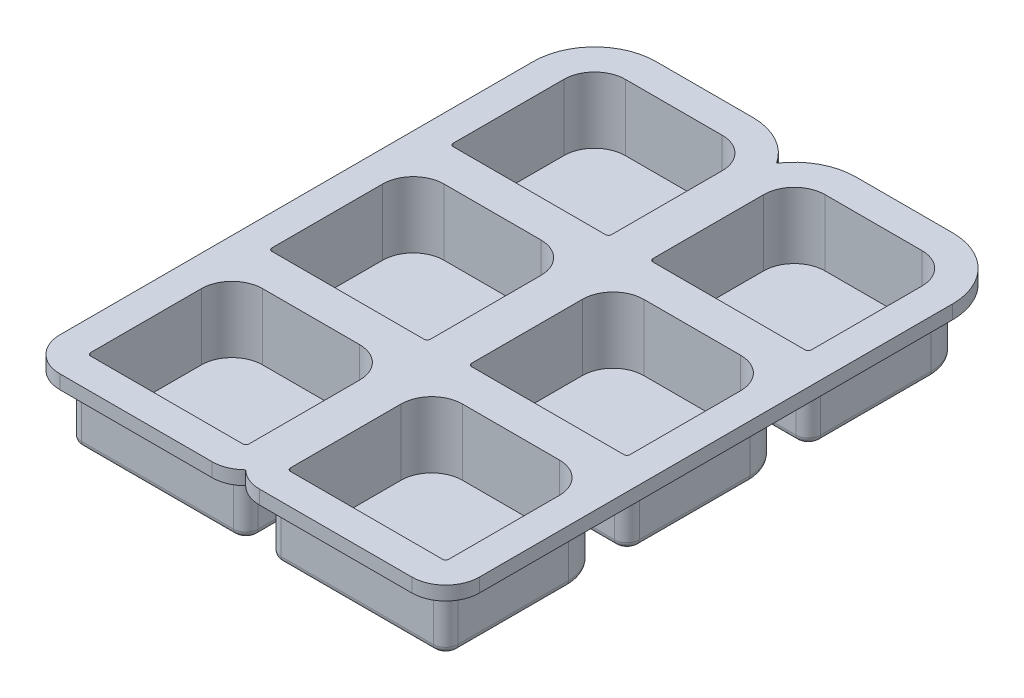
SolidWorks part; units mm, degrees
ref_plane "Alzado" through (0, 0, 0) normal (0, 0, 1) x (1, 0, 0)
ref_plane "Planta" through (0, 0, 0) normal (0, 1, 0) x (1, 0, 0)
ref_plane "Vista lateral" through (0, 0, 0) normal (1, 0, 0) x (0, 0, -1)
sketch "Croquis1" plane through (0, 0, 0) normal (0, 1, 0) x (1, 0, 0)
  line L0 (-48.265, 82.5) -> (-16.735, 82.5)
  line L1 (-6.735, 72.5) -> (-6.735, 36.5)
  line L2 (-7.735, 35.5) -> (-57.265, 35.5)
  line L3 (-58.265, 36.5) -> (-58.265, 72.5)
  line L4 (-32.5, 35.5) -> (-32.5, 82.5) construction
  line L5 (0, 97.5) -> (0, -97.5) construction
  line L6 (16.735, 82.5) -> (48.265, 82.5)
  line L7 (58.265, 72.5) -> (58.265, 36.5)
  line L8 (57.265, 35.5) -> (7.735, 35.5)
  line L9 (6.735, 36.5) -> (6.735, 72.5)
  line L10 (16.735, 23.5) -> (48.265, 23.5)
  line L11 (58.265, 13.5) -> (58.265, -22.5)
  line L12 (57.265, -23.5) -> (7.735, -23.5)
  line L13 (6.735, -22.5) -> (6.735, 13.5)
  line L14 (16.735, -35.5) -> (48.265, -35.5)
  line L15 (58.265, -45.5) -> (58.265, -81.5)
  line L16 (57.265, -82.5) -> (7.735, -82.5)
  line L17 (6.735, -81.5) -> (6.735, -45.5)
  line L18 (-48.265, 23.5) -> (-16.735, 23.5)
  line L19 (-6.735, 13.5) -> (-6.735, -22.5)
  line L20 (-7.735, -23.5) -> (-57.265, -23.5)
  line L21 (-58.265, -22.5) -> (-58.265, 13.5)
  line L22 (-48.265, -35.5) -> (-16.735, -35.5)
  line L23 (-6.735, -45.5) -> (-6.735, -81.5)
  line L24 (-7.735, -82.5) -> (-57.265, -82.5)
  line L25 (-58.265, -81.5) -> (-58.265, -45.5)
  line L26 (-48.265, 92.5) -> (-16.735, 92.5)
  line L29 (-68.265, 36.5) -> (-68.265, 72.5)
  line L32 (68.265, 72.5) -> (68.265, 36.5)
  line L33 (16.735, 92.5) -> (48.265, 92.5)
  line L34 (-68.265, -81.5) -> (-68.265, -45.5)
  line L37 (-7.735, -92.5) -> (-57.265, -92.5)
  line L40 (68.265, -45.5) -> (68.265, -81.5)
  line L41 (57.265, -92.5) -> (7.735, -92.5)
  line L42 (3.265, 72.5) -> (3.265, 36.5) construction
  line L43 (-3.265, 36.5) -> (-3.265, 72.5) construction
  line L44 (57.265, 25.5) -> (7.735, 25.5) construction
  line L45 (-7.735, 25.5) -> (-57.265, 25.5) construction
  line L46 (-48.265, -25.5) -> (-16.735, -25.5) construction
  line L47 (16.735, -25.5) -> (48.265, -25.5) construction
  line L48 (3.265, -45.5) -> (3.265, -81.5) construction
  line L49 (-3.265, -81.5) -> (-3.265, -45.5) construction
  line L50 (-68.265, 36.5) -> (-68.265, -45.5)
  line L51 (68.265, 36.5) -> (68.265, -45.5)
  arc A0 (-6.735, 72.5) -> (-16.735, 82.5) centre (-16.735, 72.5) ccw
  arc A1 (-7.735, 35.5) -> (-6.735, 36.5) centre (-7.735, 36.5) ccw
  arc A2 (-58.265, 36.5) -> (-57.265, 35.5) centre (-57.265, 36.5) ccw
  arc A3 (-48.265, 82.5) -> (-58.265, 72.5) centre (-48.265, 72.5) ccw
  arc A4 (58.265, 72.5) -> (48.265, 82.5) centre (48.265, 72.5) ccw
  arc A5 (57.265, 35.5) -> (58.265, 36.5) centre (57.265, 36.5) ccw
  arc A6 (6.735, 36.5) -> (7.735, 35.5) centre (7.735, 36.5) ccw
  arc A7 (16.735, 82.5) -> (6.735, 72.5) centre (16.735, 72.5) ccw
  arc A8 (58.265, 13.5) -> (48.265, 23.5) centre (48.265, 13.5) ccw
  arc A9 (57.265, -23.5) -> (58.265, -22.5) centre (57.265, -22.5) ccw
  arc A10 (6.735, -22.5) -> (7.735, -23.5) centre (7.735, -22.5) ccw
  arc A11 (16.735, 23.5) -> (6.735, 13.5) centre (16.735, 13.5) ccw
  arc A12 (58.265, -45.5) -> (48.265, -35.5) centre (48.265, -45.5) ccw
  arc A13 (57.265, -82.5) -> (58.265, -81.5) centre (57.265, -81.5) ccw
  arc A14 (6.735, -81.5) -> (7.735, -82.5) centre (7.735, -81.5) ccw
  arc A15 (16.735, -35.5) -> (6.735, -45.5) centre (16.735, -45.5) ccw
  arc A16 (-6.735, 13.5) -> (-16.735, 23.5) centre (-16.735, 13.5) ccw
  arc A17 (-7.735, -23.5) -> (-6.735, -22.5) centre (-7.735, -22.5) ccw
  arc A18 (-58.265, -22.5) -> (-57.265, -23.5) centre (-57.265, -22.5) ccw
  arc A19 (-48.265, 23.5) -> (-58.265, 13.5) centre (-48.265, 13.5) ccw
  arc A20 (-6.735, -45.5) -> (-16.735, -35.5) centre (-16.735, -45.5) ccw
  arc A21 (-7.735, -82.5) -> (-6.735, -81.5) centre (-7.735, -81.5) ccw
  arc A22 (-58.265, -81.5) -> (-57.265, -82.5) centre (-57.265, -81.5) ccw
  arc A23 (-48.265, -35.5) -> (-58.265, -45.5) centre (-48.265, -45.5) ccw
  arc A24 (0, 83.4517) -> (-16.735, 92.5) centre (-16.735, 72.5) ccw
  arc A27 (-48.265, 92.5) -> (-68.265, 72.5) centre (-48.265, 72.5) ccw
  arc A28 (16.735, 92.5) -> (0, 83.4517) centre (16.735, 72.5) ccw
  arc A31 (68.265, 72.5) -> (48.265, 92.5) centre (48.265, 72.5) ccw
  arc A34 (-7.735, -92.5) -> (0, -89.3211) centre (-7.735, -81.5) ccw
  arc A35 (-68.265, -81.5) -> (-57.265, -92.5) centre (-57.265, -81.5) ccw
  arc A38 (57.265, -92.5) -> (68.265, -81.5) centre (57.265, -81.5) ccw
  arc A40 (3.265, 72.5) -> (-16.735, 92.5) centre (-16.735, 72.5) ccw construction
  arc A41 (-3.265, 36.5) -> (7.735, 25.5) centre (7.735, 36.5) ccw construction
  arc A42 (-7.735, 25.5) -> (3.265, 36.5) centre (-7.735, 36.5) ccw construction
  arc A43 (16.735, 92.5) -> (-3.265, 72.5) centre (16.735, 72.5) ccw construction
  arc A44 (-68.265, 36.5) -> (-57.265, 25.5) centre (-57.265, 36.5) ccw construction
  arc A45 (57.265, 25.5) -> (68.265, 36.5) centre (57.265, 36.5) ccw construction
  arc A46 (-48.265, -25.5) -> (-68.265, -45.5) centre (-48.265, -45.5) ccw construction
  arc A47 (3.265, -45.5) -> (-16.735, -25.5) centre (-16.735, -45.5) ccw construction
  arc A48 (16.735, -25.5) -> (-3.265, -45.5) centre (16.735, -45.5) ccw construction
  arc A49 (68.265, -45.5) -> (48.265, -25.5) centre (48.265, -45.5) ccw construction
  arc A50 (-7.735, -92.5) -> (3.265, -81.5) centre (-7.735, -81.5) ccw construction
  arc A51 (-3.265, -81.5) -> (7.735, -92.5) centre (7.735, -81.5) ccw construction
  arc A52 (0, -89.3211) -> (7.735, -92.5) centre (7.735, -81.5) ccw
  point P15 (-58.265, 0)
  point P26 (0, 0)
  dimension "D2" = 10
  dimension "D4" = 1
  dimension "D1" = 31.53
  dimension "D3" = 36
  dimension "D5" = 49.53
  dimension "D6" = 2
  dimension "D8" = 195
  dimension "D9" = 165
  dimension "D10" = 82.5
  dimension "D11" = 32.5
  dimension "D12" = 10
  dimension "D7" = 3
extrude "Saliente-Extruir1" add sketch "Croquis1" along normal blind 21.5
sketch "Croquis2" plane through (0, 0, 0) normal (0, -1, 0) x (1, 0, 0)
  line L22 (61.265, -72.5) -> (61.265, -36.5)
  line L23 (16.735, -85.5) -> (48.265, -85.5)
  line L24 (3.735, -36.5) -> (3.735, -72.5)
  line L25 (57.265, -32.5) -> (7.735, -32.5)
  line L26 (61.265, -72.5) -> (61.265, -36.5)
  line L27 (16.735, -85.5) -> (48.265, -85.5)
  line L28 (3.735, -36.5) -> (3.735, -72.5)
  line L29 (57.265, -32.5) -> (7.735, -32.5)
  line L32 (-48.265, -92.5) -> (-16.735, -92.5)
  line L33 (16.735, -92.5) -> (48.265, -92.5)
  line L34 (68.265, -72.5) -> (68.265, 81.5)
  line L35 (-3.735, -72.5) -> (-3.735, -36.5)
  line L36 (-48.265, -85.5) -> (-16.735, -85.5)
  line L37 (-61.265, -36.5) -> (-61.265, -72.5)
  line L38 (-7.735, -32.5) -> (-57.265, -32.5)
  line L39 (-3.735, -72.5) -> (-3.735, -36.5)
  line L40 (-48.265, -85.5) -> (-16.735, -85.5)
  line L41 (-61.265, -36.5) -> (-61.265, -72.5)
  line L42 (-7.735, -32.5) -> (-57.265, -32.5)
  line L43 (57.265, 92.5) -> (7.735, 92.5)
  line L44 (-7.735, 92.5) -> (-57.265, 92.5)
  line L45 (-68.265, 81.5) -> (-68.265, -72.5)
  line L46 (-48.265, -92.5) -> (-16.735, -92.5)
  line L47 (16.735, -92.5) -> (48.265, -92.5)
  line L48 (-48.265, 32.5) -> (-16.735, 32.5)
  line L49 (-3.735, 45.5) -> (-3.735, 81.5)
  line L50 (-61.265, 81.5) -> (-61.265, 45.5)
  line L51 (-7.735, 85.5) -> (-57.265, 85.5)
  line L52 (-48.265, 32.5) -> (-16.735, 32.5)
  line L53 (-3.735, 45.5) -> (-3.735, 81.5)
  line L54 (-61.265, 81.5) -> (-61.265, 45.5)
  line L55 (-7.735, 85.5) -> (-57.265, 85.5)
  line L56 (68.265, -72.5) -> (68.265, 81.5)
  line L57 (57.265, 92.5) -> (7.735, 92.5)
  line L58 (-7.735, 92.5) -> (-57.265, 92.5)
  line L59 (-68.265, 81.5) -> (-68.265, -72.5)
  line L75 (16.735, 32.5) -> (48.265, 32.5)
  line L76 (61.265, 45.5) -> (61.265, 81.5)
  line L77 (57.265, 85.5) -> (7.735, 85.5)
  line L78 (3.735, 81.5) -> (3.735, 45.5)
  line L79 (16.735, 32.5) -> (48.265, 32.5)
  line L80 (61.265, 45.5) -> (61.265, 81.5)
  line L81 (57.265, 85.5) -> (7.735, 85.5)
  line L82 (3.735, 81.5) -> (3.735, 45.5)
  line L99 (-7.735, 26.5) -> (-57.265, 26.5)
  line L100 (-3.735, -13.5) -> (-3.735, 22.5)
  line L101 (-48.265, -26.5) -> (-16.735, -26.5)
  line L102 (-61.265, 22.5) -> (-61.265, -13.5)
  line L103 (-7.735, 26.5) -> (-57.265, 26.5)
  line L104 (-3.735, -13.5) -> (-3.735, 22.5)
  line L105 (-48.265, -26.5) -> (-16.735, -26.5)
  line L106 (-61.265, 22.5) -> (-61.265, -13.5)
  line L123 (57.265, 26.5) -> (7.735, 26.5)
  line L124 (61.265, -13.5) -> (61.265, 22.5)
  line L125 (16.735, -26.5) -> (48.265, -26.5)
  line L126 (3.735, 22.5) -> (3.735, -13.5)
  line L127 (57.265, 26.5) -> (7.735, 26.5)
  line L128 (61.265, -13.5) -> (61.265, 22.5)
  line L129 (16.735, -26.5) -> (48.265, -26.5)
  line L130 (3.735, 22.5) -> (3.735, -13.5)
  arc A19 (48.265, -85.5) -> (61.265, -72.5) centre (48.265, -72.5) ccw
  arc A20 (61.265, -36.5) -> (57.265, -32.5) centre (57.265, -36.5) ccw
  arc A21 (3.735, -72.5) -> (16.735, -85.5) centre (16.735, -72.5) ccw
  arc A22 (7.735, -32.5) -> (3.735, -36.5) centre (7.735, -36.5) ccw
  arc A23 (48.265, -85.5) -> (61.265, -72.5) centre (48.265, -72.5) ccw
  arc A24 (61.265, -36.5) -> (57.265, -32.5) centre (57.265, -36.5) ccw
  arc A25 (3.735, -72.5) -> (16.735, -85.5) centre (16.735, -72.5) ccw
  arc A26 (7.735, -32.5) -> (3.735, -36.5) centre (7.735, -36.5) ccw
  arc A31 (-68.265, -72.5) -> (-48.265, -92.5) centre (-48.265, -72.5) ccw
  arc A32 (-16.735, -92.5) -> (0, -83.4517) centre (-16.735, -72.5) ccw
  arc A33 (0, -83.4517) -> (16.735, -92.5) centre (16.735, -72.5) ccw
  arc A34 (48.265, -92.5) -> (68.265, -72.5) centre (48.265, -72.5) ccw
  arc A35 (-3.735, -36.5) -> (-7.735, -32.5) centre (-7.735, -36.5) ccw
  arc A36 (-16.735, -85.5) -> (-3.735, -72.5) centre (-16.735, -72.5) ccw
  arc A37 (-61.265, -72.5) -> (-48.265, -85.5) centre (-48.265, -72.5) ccw
  arc A38 (-57.265, -32.5) -> (-61.265, -36.5) centre (-57.265, -36.5) ccw
  arc A39 (-3.735, -36.5) -> (-7.735, -32.5) centre (-7.735, -36.5) ccw
  arc A40 (-16.735, -85.5) -> (-3.735, -72.5) centre (-16.735, -72.5) ccw
  arc A41 (-61.265, -72.5) -> (-48.265, -85.5) centre (-48.265, -72.5) ccw
  arc A42 (-57.265, -32.5) -> (-61.265, -36.5) centre (-57.265, -36.5) ccw
  arc A43 (68.265, 81.5) -> (57.265, 92.5) centre (57.265, 81.5) ccw
  arc A44 (-61.265, 45.5) -> (-48.265, 32.5) centre (-48.265, 45.5) ccw
  arc A45 (-16.735, 32.5) -> (-3.735, 45.5) centre (-16.735, 45.5) ccw
  arc A46 (-3.735, 81.5) -> (-7.735, 85.5) centre (-7.735, 81.5) ccw
  arc A47 (-57.265, 85.5) -> (-61.265, 81.5) centre (-57.265, 81.5) ccw
  arc A48 (-61.265, 45.5) -> (-48.265, 32.5) centre (-48.265, 45.5) ccw
  arc A49 (-16.735, 32.5) -> (-3.735, 45.5) centre (-16.735, 45.5) ccw
  arc A50 (-3.735, 81.5) -> (-7.735, 85.5) centre (-7.735, 81.5) ccw
  arc A51 (-57.265, 85.5) -> (-61.265, 81.5) centre (-57.265, 81.5) ccw
  arc A52 (7.735, 92.5) -> (0, 89.3211) centre (7.735, 81.5) ccw
  arc A53 (0, 89.3211) -> (-7.735, 92.5) centre (-7.735, 81.5) ccw
  arc A54 (-57.265, 92.5) -> (-68.265, 81.5) centre (-57.265, 81.5) ccw
  arc A55 (-68.265, -72.5) -> (-48.265, -92.5) centre (-48.265, -72.5) ccw
  arc A56 (-16.735, -92.5) -> (0, -83.4517) centre (-16.735, -72.5) ccw
  arc A57 (0, -83.4517) -> (16.735, -92.5) centre (16.735, -72.5) ccw
  arc A58 (48.265, -92.5) -> (68.265, -72.5) centre (48.265, -72.5) ccw
  arc A59 (68.265, 81.5) -> (57.265, 92.5) centre (57.265, 81.5) ccw
  arc A60 (7.735, 92.5) -> (0, 89.3211) centre (7.735, 81.5) ccw
  arc A61 (0, 89.3211) -> (-7.735, 92.5) centre (-7.735, 81.5) ccw
  arc A62 (-57.265, 92.5) -> (-68.265, 81.5) centre (-57.265, 81.5) ccw
  arc A69 (48.265, 32.5) -> (61.265, 45.5) centre (48.265, 45.5) ccw
  arc A70 (3.735, 45.5) -> (16.735, 32.5) centre (16.735, 45.5) ccw
  arc A71 (61.265, 81.5) -> (57.265, 85.5) centre (57.265, 81.5) ccw
  arc A72 (7.735, 85.5) -> (3.735, 81.5) centre (7.735, 81.5) ccw
  arc A73 (48.265, 32.5) -> (61.265, 45.5) centre (48.265, 45.5) ccw
  arc A74 (3.735, 45.5) -> (16.735, 32.5) centre (16.735, 45.5) ccw
  arc A75 (61.265, 81.5) -> (57.265, 85.5) centre (57.265, 81.5) ccw
  arc A76 (7.735, 85.5) -> (3.735, 81.5) centre (7.735, 81.5) ccw
  arc A97 (-3.735, 22.5) -> (-7.735, 26.5) centre (-7.735, 22.5) ccw
  arc A98 (-16.735, -26.5) -> (-3.735, -13.5) centre (-16.735, -13.5) ccw
  arc A99 (-61.265, -13.5) -> (-48.265, -26.5) centre (-48.265, -13.5) ccw
  arc A100 (-57.265, 26.5) -> (-61.265, 22.5) centre (-57.265, 22.5) ccw
  arc A101 (-3.735, 22.5) -> (-7.735, 26.5) centre (-7.735, 22.5) ccw
  arc A102 (-16.735, -26.5) -> (-3.735, -13.5) centre (-16.735, -13.5) ccw
  arc A103 (-61.265, -13.5) -> (-48.265, -26.5) centre (-48.265, -13.5) ccw
  arc A104 (-57.265, 26.5) -> (-61.265, 22.5) centre (-57.265, 22.5) ccw
  arc A125 (61.265, 22.5) -> (57.265, 26.5) centre (57.265, 22.5) ccw
  arc A126 (48.265, -26.5) -> (61.265, -13.5) centre (48.265, -13.5) ccw
  arc A127 (3.735, -13.5) -> (16.735, -26.5) centre (16.735, -13.5) ccw
  arc A128 (7.735, 26.5) -> (3.735, 22.5) centre (7.735, 22.5) ccw
  arc A129 (61.265, 22.5) -> (57.265, 26.5) centre (57.265, 22.5) ccw
  arc A130 (48.265, -26.5) -> (61.265, -13.5) centre (48.265, -13.5) ccw
  arc A131 (3.735, -13.5) -> (16.735, -26.5) centre (16.735, -13.5) ccw
  arc A132 (7.735, 26.5) -> (3.735, 22.5) centre (7.735, 22.5) ccw
  dimension "D1" = 3
  dimension "D2" = 3
  dimension "D3" = 3
  dimension "D4" = 3
  dimension "D5" = 3
  dimension "D6" = 3
  dimension "D7" = 0
extrude "Cortar-Extruir1" cut sketch "Croquis2" against normal blind 17
sketch "Croquis3" plane through (0, 0, 0) normal (0, -1, 0) x (1, 0, 0)
  line L4 (61.265, 45.5) -> (61.265, 81.5)
  line L5 (57.265, 85.5) -> (7.735, 85.5)
  line L6 (3.735, 81.5) -> (3.735, 45.5)
  line L7 (16.735, 32.5) -> (48.265, 32.5)
  line L8 (61.265, 45.5) -> (61.265, 81.5)
  line L9 (57.265, 85.5) -> (7.735, 85.5)
  line L10 (3.735, 81.5) -> (3.735, 45.5)
  line L11 (16.735, 32.5) -> (48.265, 32.5)
  line L12 (-48.265, 32.5) -> (-16.735, 32.5)
  line L13 (-3.735, 45.5) -> (-3.735, 81.5)
  line L14 (-7.735, 85.5) -> (-57.265, 85.5)
  line L15 (-61.265, 81.5) -> (-61.265, 45.5)
  line L16 (-48.265, 32.5) -> (-16.735, 32.5)
  line L17 (-3.735, 45.5) -> (-3.735, 81.5)
  line L18 (-7.735, 85.5) -> (-57.265, 85.5)
  line L19 (-61.265, 81.5) -> (-61.265, 45.5)
  line L20 (-7.735, 26.5) -> (-57.265, 26.5)
  line L21 (-61.265, 22.5) -> (-61.265, -13.5)
  line L22 (-48.265, -26.5) -> (-16.735, -26.5)
  line L23 (-3.735, -13.5) -> (-3.735, 22.5)
  line L24 (-7.735, 26.5) -> (-57.265, 26.5)
  line L25 (-61.265, 22.5) -> (-61.265, -13.5)
  line L26 (-48.265, -26.5) -> (-16.735, -26.5)
  line L27 (-3.735, -13.5) -> (-3.735, 22.5)
  line L28 (57.265, 26.5) -> (7.735, 26.5)
  line L29 (3.735, 22.5) -> (3.735, -13.5)
  line L30 (16.735, -26.5) -> (48.265, -26.5)
  line L31 (61.265, -13.5) -> (61.265, 22.5)
  line L32 (57.265, 26.5) -> (7.735, 26.5)
  line L33 (3.735, 22.5) -> (3.735, -13.5)
  line L34 (16.735, -26.5) -> (48.265, -26.5)
  line L35 (61.265, -13.5) -> (61.265, 22.5)
  line L36 (-7.735, -32.5) -> (-57.265, -32.5)
  line L37 (-61.265, -36.5) -> (-61.265, -72.5)
  line L38 (-48.265, -85.5) -> (-16.735, -85.5)
  line L39 (-3.735, -72.5) -> (-3.735, -36.5)
  line L40 (-7.735, -32.5) -> (-57.265, -32.5)
  line L41 (-61.265, -36.5) -> (-61.265, -72.5)
  line L42 (-48.265, -85.5) -> (-16.735, -85.5)
  line L43 (-3.735, -72.5) -> (-3.735, -36.5)
  line L44 (61.265, -72.5) -> (61.265, -36.5)
  line L45 (57.265, -32.5) -> (7.735, -32.5)
  line L46 (3.735, -36.5) -> (3.735, -72.5)
  line L47 (16.735, -85.5) -> (48.265, -85.5)
  line L48 (61.265, -72.5) -> (61.265, -36.5)
  line L49 (57.265, -32.5) -> (7.735, -32.5)
  line L50 (3.735, -36.5) -> (3.735, -72.5)
  line L51 (16.735, -85.5) -> (48.265, -85.5)
  arc A4 (48.265, 32.5) -> (61.265, 45.5) centre (48.265, 45.5) ccw
  arc A5 (61.265, 81.5) -> (57.265, 85.5) centre (57.265, 81.5) ccw
  arc A6 (7.735, 85.5) -> (3.735, 81.5) centre (7.735, 81.5) ccw
  arc A7 (3.735, 45.5) -> (16.735, 32.5) centre (16.735, 45.5) ccw
  arc A8 (48.265, 32.5) -> (61.265, 45.5) centre (48.265, 45.5) ccw
  arc A9 (61.265, 81.5) -> (57.265, 85.5) centre (57.265, 81.5) ccw
  arc A10 (7.735, 85.5) -> (3.735, 81.5) centre (7.735, 81.5) ccw
  arc A11 (3.735, 45.5) -> (16.735, 32.5) centre (16.735, 45.5) ccw
  arc A12 (-61.265, 45.5) -> (-48.265, 32.5) centre (-48.265, 45.5) ccw
  arc A13 (-16.735, 32.5) -> (-3.735, 45.5) centre (-16.735, 45.5) ccw
  arc A14 (-3.735, 81.5) -> (-7.735, 85.5) centre (-7.735, 81.5) ccw
  arc A15 (-57.265, 85.5) -> (-61.265, 81.5) centre (-57.265, 81.5) ccw
  arc A16 (-61.265, 45.5) -> (-48.265, 32.5) centre (-48.265, 45.5) ccw
  arc A17 (-16.735, 32.5) -> (-3.735, 45.5) centre (-16.735, 45.5) ccw
  arc A18 (-3.735, 81.5) -> (-7.735, 85.5) centre (-7.735, 81.5) ccw
  arc A19 (-57.265, 85.5) -> (-61.265, 81.5) centre (-57.265, 81.5) ccw
  arc A20 (-3.735, 22.5) -> (-7.735, 26.5) centre (-7.735, 22.5) ccw
  arc A21 (-57.265, 26.5) -> (-61.265, 22.5) centre (-57.265, 22.5) ccw
  arc A22 (-61.265, -13.5) -> (-48.265, -26.5) centre (-48.265, -13.5) ccw
  arc A23 (-16.735, -26.5) -> (-3.735, -13.5) centre (-16.735, -13.5) ccw
  arc A24 (-3.735, 22.5) -> (-7.735, 26.5) centre (-7.735, 22.5) ccw
  arc A25 (-57.265, 26.5) -> (-61.265, 22.5) centre (-57.265, 22.5) ccw
  arc A26 (-61.265, -13.5) -> (-48.265, -26.5) centre (-48.265, -13.5) ccw
  arc A27 (-16.735, -26.5) -> (-3.735, -13.5) centre (-16.735, -13.5) ccw
  arc A28 (61.265, 22.5) -> (57.265, 26.5) centre (57.265, 22.5) ccw
  arc A29 (7.735, 26.5) -> (3.735, 22.5) centre (7.735, 22.5) ccw
  arc A30 (3.735, -13.5) -> (16.735, -26.5) centre (16.735, -13.5) ccw
  arc A31 (48.265, -26.5) -> (61.265, -13.5) centre (48.265, -13.5) ccw
  arc A32 (61.265, 22.5) -> (57.265, 26.5) centre (57.265, 22.5) ccw
  arc A33 (7.735, 26.5) -> (3.735, 22.5) centre (7.735, 22.5) ccw
  arc A34 (3.735, -13.5) -> (16.735, -26.5) centre (16.735, -13.5) ccw
  arc A35 (48.265, -26.5) -> (61.265, -13.5) centre (48.265, -13.5) ccw
  arc A36 (-3.735, -36.5) -> (-7.735, -32.5) centre (-7.735, -36.5) ccw
  arc A37 (-57.265, -32.5) -> (-61.265, -36.5) centre (-57.265, -36.5) ccw
  arc A38 (-61.265, -72.5) -> (-48.265, -85.5) centre (-48.265, -72.5) ccw
  arc A39 (-16.735, -85.5) -> (-3.735, -72.5) centre (-16.735, -72.5) ccw
  arc A40 (-3.735, -36.5) -> (-7.735, -32.5) centre (-7.735, -36.5) ccw
  arc A41 (-57.265, -32.5) -> (-61.265, -36.5) centre (-57.265, -36.5) ccw
  arc A42 (-61.265, -72.5) -> (-48.265, -85.5) centre (-48.265, -72.5) ccw
  arc A43 (-16.735, -85.5) -> (-3.735, -72.5) centre (-16.735, -72.5) ccw
  arc A44 (48.265, -85.5) -> (61.265, -72.5) centre (48.265, -72.5) ccw
  arc A45 (61.265, -36.5) -> (57.265, -32.5) centre (57.265, -36.5) ccw
  arc A46 (7.735, -32.5) -> (3.735, -36.5) centre (7.735, -36.5) ccw
  arc A47 (3.735, -72.5) -> (16.735, -85.5) centre (16.735, -72.5) ccw
  arc A48 (48.265, -85.5) -> (61.265, -72.5) centre (48.265, -72.5) ccw
  arc A49 (61.265, -36.5) -> (57.265, -32.5) centre (57.265, -36.5) ccw
  arc A50 (7.735, -32.5) -> (3.735, -36.5) centre (7.735, -36.5) ccw
  arc A51 (3.735, -72.5) -> (16.735, -85.5) centre (16.735, -72.5) ccw
  dimension "D1" = 0
  dimension "D2" = 0
  dimension "D3" = 0
  dimension "D4" = 0
  dimension "D5" = 0
  dimension "D6" = 0
extrude "Saliente-Extruir2" add sketch "Croquis3" along normal blind 3
fillet "Redondeo2" radius 2 96 edges at (-57.4574, -3, 36.3076) (-61.265, -3, 63.5) (-60.0934, -3, 84.3284) (-32.5, -3, 85.5) (-4.9066, -3, 84.3284) (-3.735, -3, 63.5) (-7.5426, -3, 36.3076) (7.5426, -3, 36.3076) (3.735, -3, 63.5) (4.9066, -3, 84.3284) (32.5, -3, 85.5) (60.0934, -3, 84.3284) (61.265, -3, 63.5) (57.4574, -3, 36.3076) (-57.4574, -3, -22.6924) (-61.265, -3, 4.5) (-60.0934, -3, 25.3284) (-32.5, -3, 26.5) (-4.9066, -3, 25.3284) (-3.735, -3, 4.5) (-7.5426, -3, -22.6924) (7.5426, -3, -22.6924) (3.735, -3, 4.5) (4.9066, -3, 25.3284) (32.5, -3, 26.5) (60.0934, -3, 25.3284) (61.265, -3, 4.5) (57.4574, -3, -22.6924) (-57.4574, -3, -81.6924) (-61.265, -3, -54.5) (-60.0934, -3, -33.6716) (-32.5, -3, -32.5) (-4.9066, -3, -33.6716) (-3.735, -3, -54.5) (-7.5426, -3, -81.6924) (7.5426, -3, -81.6924) (3.735, -3, -54.5) (4.9066, -3, -33.6716) (32.5, -3, -32.5) (60.0934, -3, -33.6716) (61.265, -3, -54.5) (57.4574, -3, -81.6924) (-32.5, -3, 32.5) (32.5, -3, 32.5) (-32.5, -3, -26.5) (32.5, -3, -26.5) (-32.5, -3, -85.5) (32.5, -3, -85.5) (4.9066, 17, 84.3284) (32.5, 17, 85.5) (60.0934, 17, 84.3284) (61.265, 17, 63.5) (57.4574, 17, 36.3076) (32.5, 17, 32.5) (7.5426, 17, 36.3076) (4.9066, 17, 25.3284) (32.5, 17, 26.5) (60.0934, 17, 25.3284) (61.265, 17, 4.5) (57.4574, 17, -22.6924) (32.5, 17, -26.5) (7.5426, 17, -22.6924) (-60.0934, 17, 84.3284) (-32.5, 17, 85.5) (-4.9066, 17, 84.3284) (-3.735, 17, 63.5) (-7.5426, 17, 36.3076) (-32.5, 17, 32.5) (-57.4574, 17, 36.3076) (-60.0934, 17, 25.3284) (-32.5, 17, 26.5) (-4.9066, 17, 25.3284) (-3.735, 17, 4.5) (-7.5426, 17, -22.6924) (-32.5, 17, -26.5) (-57.4574, 17, -22.6924) (7.5426, 17, -81.6924) (3.735, 17, -54.5) (4.9066, 17, -33.6716) (32.5, 17, -32.5) (60.0934, 17, -33.6716) (61.265, 17, -54.5) (57.4574, 17, -81.6924) (-60.0934, 17, -33.6716) (-32.5, 17, -32.5) (-4.9066, 17, -33.6716) (-3.735, 17, -54.5) (-7.5426, 17, -81.6924) (-32.5, 17, -85.5) (-57.4574, 17, -81.6924) (3.735, 17, 63.5) (3.735, 17, 4.5) (-61.265, 17, 63.5) (-61.265, 17, 4.5) (32.5, 17, -85.5) (-61.265, 17, -54.5)
